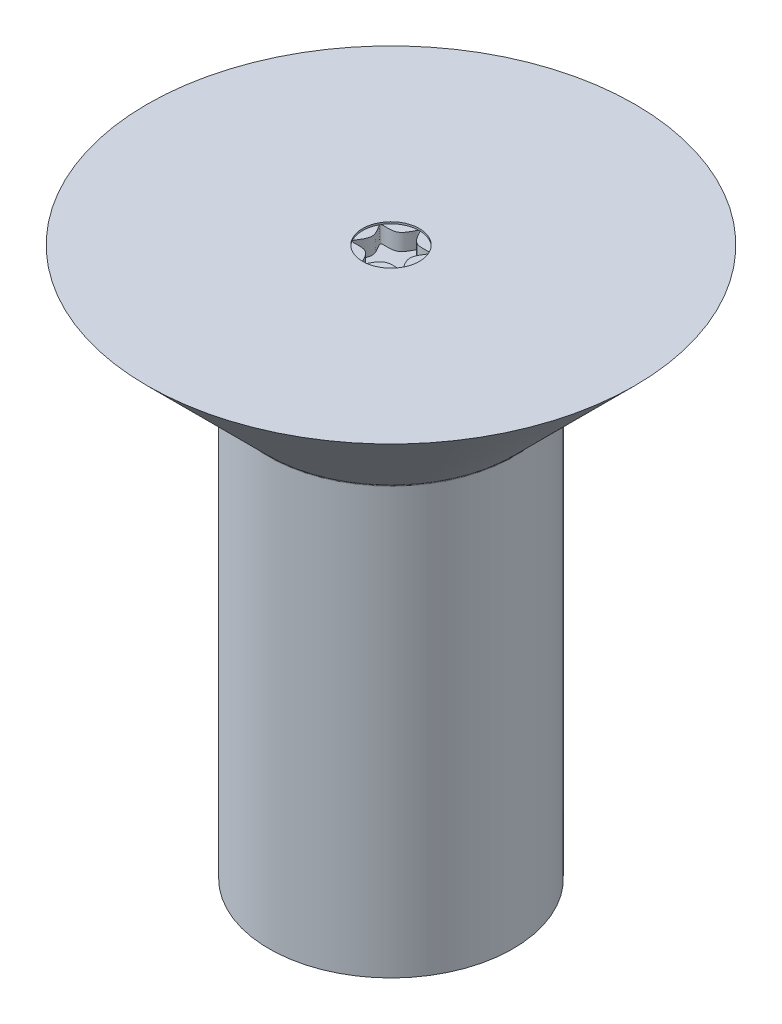
SolidWorks part; units mm, degrees
ref_plane "Front" through (0, 0, 0) normal (0, 0, 1) x (1, 0, 0)
ref_plane "Top" through (0, 0, 0) normal (0, 1, 0) x (1, 0, 0)
ref_plane "Right" through (0, 0, 0) normal (1, 0, 0) x (0, 0, -1)
other "Configuration Table"
sketch "Sketch1" plane through (0, 0, 0) normal (0, 0, 1) x (1, 0, 0)
  line L0 (0, 0) -> (0, 8.8882) construction
  line L1 (0, 27) -> (12, 27)
  line L2 (6, 0) -> (6, 21)
  line L3 (6, 21) -> (12, 21) construction
  line L4 (12, 21) -> (12, 15) construction
  line L5 (6, 0) -> (0, 0)
  line L6 (0, 0) -> (0, 27)
  line L7 (12, 27) -> (6, 21)
  dimension "head_dia" = 24
  dimension "head_ht" = 6
  dimension "length" = 27
  dimension "D1" = 45
  dimension "pitch" = 6
  dimension "thread_gap" = 6
revolve "Body-Revolve" add sketch "Sketch1" angle 360 about L0
cosmetic thread "ThreadCosmetic" [suppressed] parameters "D1"=15, "D2"=5.505
sketch "Sketch2" plane through (0, 27, 0) normal (0, 1, 0) x (-1, 0, 0)
  line L0 (0, 0) -> (0, -1.54)
  line L1 (0, 0) -> (-0.7, -1.2124)
  circle A0 centre (0, 0) radius 1.4
  circle A1 centre (0, 0) radius 0.9333
  spline S0 degree 3 poles (0.302, -0.523) (0, -1.8385) (-0.302, -0.523) (-1.5922, -0.9193) (-0.6039, 0) (-1.5922, 0.9193) (-0.302, 0.523) (0, 1.8385) (0.302, 0.523) (1.5922, 0.9193) (0.6039, 0) (1.5922, -0.9193) (0.302, -0.523) (0, -1.8385) (-0.302, -0.523) knots -0.25 -0.166667 -0.083333 0 0.083333 0.166667 0.25 0.333333 0.416667 0.5 0.583333 0.666667 0.75 0.833333 0.916667 1 1.083333 1.166667 1.25 only from (0, -1.4) to (0, -1.4)
  point P4 (0, -1.4)
  point P7 (-0.4667, -0.8083)
  point P10 (-1.2124, -0.7)
  point P11 (-1.2124, 0.7)
  point P12 (0, 1.4)
  point P13 (1.2124, 0.7)
  point P14 (1.2124, -0.7)
  point P15 (-0.9333, 0)
  point P16 (-0.4667, 0.8083)
  point P17 (0.4667, 0.8083)
  point P18 (0.9333, 0)
  point P19 (0.4667, -0.8083)
  dimension "socket_dia" = 2.8
  dimension "D1" = 1.8667
  dimension "D2" = 30
  dimension "D3" = 1.54
extrude "Recess-Cut-Extrude1" cut sketch "Sketch2" against normal blind 0.91 contours S0
sketch "Sketch3" plane through (0, 27, 0) normal (0, 1, 0) x (-1, 0, 0)
  circle A0 centre (0, 0) radius 1.4
  dimension "D1" = 2.8
extrude "Recess-Cut-Extrude2" cut sketch "Sketch3" against normal blind 0.091
sketch "Sketch4" plane through (4.7999, 0, 0) normal (0, 0, 1) x (1, 0, 0)
  line L0 (0, 26.09) -> (0.9333, 26.09)
  line L2 (0.9333, 26.09) -> (0, 21.6)
  line L4 (0, 21.6) -> (0, 26.09)
  dimension "D2" = 0.9333
revolve "Drill-Cut-Revolve" cut sketch "Sketch4" angle 360 about axis through (0, 0, 0) along (0, 1, 0)
fillet "Fillet1" radius 0.1 1 edges at (0, 21, -6)
sketch "Sketch5" plane through (0, 0, 0) normal (0, 0, 1) x (1, 0, 0)
  line L0 (6, 15) -> (6, 11.2501)
  line L1 (6, 0) -> (6, 20.9586) construction
  line L2 (6, 11.2501) -> (2.7525, 13.1251)
  line L3 (2.7525, 13.1251) -> (6, 15)
  line L4 (0, 0) -> (0, 8.8882) construction
  line L5 (-6, 0) -> (6, 0) construction
  dimension "D1" = 2.7525
  dimension "D2" = 15
revolve "ThreadSchematic" [suppressed] cut sketch "Sketch5" angle 360 about axis through (0, 0, 0) along (0, 1, 0)
pattern_linear "ThdSchPat" [suppressed] count 3 spacing 6 along (0, 1, 0)
sketch "Sketch6" plane through (0, 0, 0) normal (0, 0, 1) x (1, 0, 0)
  line L0 (0.01, 0) -> (6, 0)
  line L1 (-6, 0) -> (6, 0) construction
  line L2 (6, 0) -> (6, 2.6)
  line L4 (6, 2.6) -> (0.01, 0)
  line L5 (0, 0) -> (0, 8.8882) construction
  dimension "D1" = 6
  dimension "end_lengthC" = 2.6
revolve "TypeC" [suppressed] cut sketch "Sketch6" angle 360 about axis through (0, 0, 0) along (0, 1, 0)
sketch "Sketch7" plane through (0, 0, 0) normal (0, 0, 1) x (1, 0, 0)
  line L0 (5.7793, 0) -> (6, 0)
  line L1 (0, 0) -> (0, 8.8882) construction
  line L2 (6, 0) -> (6, 2.1)
  line L4 (6, 2.1) -> (5.7793, 0)
  line L5 (-6, 0) -> (6, 0) construction
  dimension "D1" = 6
  dimension "end_lengthF" = 2.1
  dimension "D2" = 6
revolve "TypeF" [suppressed] cut sketch "Sketch7" angle 360 about axis through (0, 0, 0) along (0, 1, 0)
sketch "Sketch8" plane through (0, 0, 0) normal (0, 0, 1) x (1, 0, 0)
  line L0 (6, -0.09) -> (6, 2)
  line L2 (6, 2) -> (0.0633, 0.0054)
  line L3 (0.03, 0) -> (0.03, -0.09)
  line L4 (0.03, -0.09) -> (6, -0.09)
  line L5 (0, 0) -> (0, 8.8882) construction
  line L9 (-6, 0) -> (6, 0) construction
  arc A0 (0.0633, 0.0054) -> (0.03, 0) centre (0.03, 0.1045) cw
  dimension "D3" = 6
  dimension "D4" = 0.1045
  dimension "end_lengthR" = 2.09
revolve "TypeR" [suppressed] cut sketch "Sketch8" angle 360 about axis through (0, 0, 0) along (0, 1, 0)
equation "\"thread_gap@Sketch1\" = \"pitch@Sketch1\""
equation "\"D1@ThreadCosmetic\" = \"length@Sketch1\" - \"head_ht@Sketch1\" - \"thread_gap@Sketch1\""
equation "\"D2@ThreadCosmetic\" = \"head_dia@Sketch1\" - \"head_ht@Sketch1\" * 2 - 1.0825 * \"pitch@Sketch1\""
equation "\"D1@Sketch2\" = \"socket_dia@Sketch2\" / 1.5"
equation "\"D3@Sketch2\" = \"socket_dia@Sketch2\" / 2 * 1.1"
equation "\"D1@Sketch3\" = \"socket_dia@Sketch2\""
equation "\"D1@Recess-Cut-Extrude2\" = 0.1 * \"socket-dep@Recess-Cut-Extrude1\""
equation "\"D2@Sketch4\" = \"D1@Sketch2\" / 2"
equation "\"D1@Sketch5\" = \"D2@ThreadCosmetic\" / 2"
equation "\"D2@Sketch5\" = \"D1@ThreadCosmetic\""
equation "\"D3@ThdSchPat\" = \"pitch@Sketch1\""
equation "\"D1@ThdSchPat\" = \"D1@ThreadCosmetic\" / \"D3@ThdSchPat\""
equation "\"D1@Sketch6\" = \"head_dia@Sketch1\" / 2 - \"head_ht@Sketch1\""
equation "\"D2@Sketch7\" = \"head_dia@Sketch1\" / 2 - \"head_ht@Sketch1\""
equation "\"D3@Sketch8\" = \"head_dia@Sketch1\" * 0.5 - \"head_ht@Sketch1\""
equation "\"D4@Sketch8\" = \"end_lengthR@Sketch8\" / 20"
